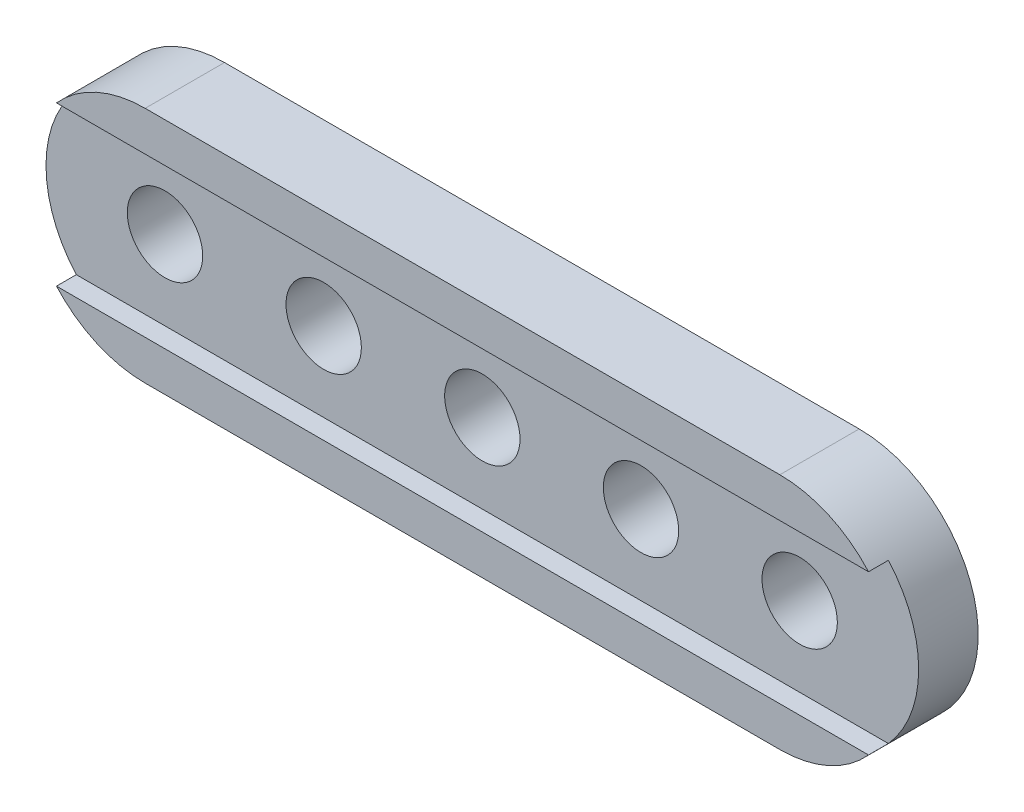
SolidWorks part; units mm, degrees
ref_plane "前视基准面" through (0, 0, 0) normal (0, 0, 1) x (1, 0, 0)
ref_plane "上视基准面" through (0, 0, 0) normal (0, 1, 0) x (1, 0, 0)
ref_plane "右视基准面" through (0, 0, 0) normal (1, 0, 0) x (0, 0, -1)
sketch "草图1" plane through (0, 0, 0) normal (0, 0, 1) x (1, 0, 0)
  line L0 (-16, 0) -> (16, 0) construction
  line L1 (-16, 6) -> (16, 6)
  line L2 (-16, -6) -> (16, -6)
  arc A0 (-16, 6) -> (-16, -6) centre (-16, 0) ccw
  arc A1 (16, -6) -> (16, 6) centre (16, 0) ccw
  point P3 (0, 0)
  point P8 (0, 0)
  dimension "D2" = 6
  dimension "D1" = 32
extrude "凸台-拉伸1" add sketch "草图1" along normal blind 4
sketch "草图2" plane through (0, 0, 4) normal (0, 0, 1) x (1, 0, 0)
  line L1 (-22, 4) -> (22, 4)
  line L2 (-22, 4) -> (-22, -4)
  line L3 (-22, -4) -> (22, -4)
  line L4 (22, 4) -> (22, -4)
  arc A0 (-16, 6) -> (-16, -6) centre (-16, 0) ccw construction
  arc A1 (16, -6) -> (16, 6) centre (16, 0) ccw construction
  point P10 (22, 0)
  dimension "D1" = 8
extrude "切除-拉伸1" cut sketch "草图2" against normal blind 1
sketch "草图3" plane through (0, 0, 3) normal (0, 0, 1) x (1, 0, 0)
  circle A0 centre (-16, 0) radius 1.9
  arc A1 (-20.4721, 4) -> (-20.4721, -4) centre (-16, 0) ccw construction
  dimension "D1" = 4.1
extrude "切除-拉伸2" cut sketch "草图3" against normal blind 3
pattern_linear "阵列(线性)1" count 5 spacing 8 along (1, 0, 0) of "切除-拉伸2"
